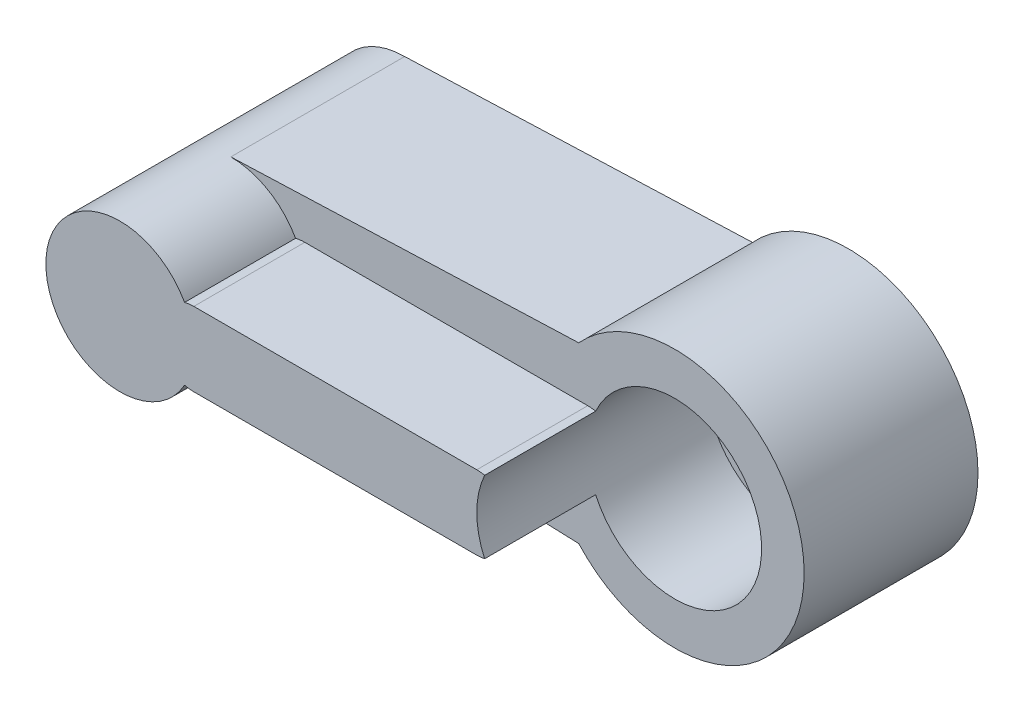
SolidWorks part; units mm, degrees
ref_plane "Front Plane" through (0, 0, 0) normal (0, 0, 1) x (1, 0, 0)
ref_plane "Top Plane" through (0, 0, 0) normal (0, 1, 0) x (1, 0, 0)
ref_plane "Right Plane" through (0, 0, 0) normal (1, 0, 0) x (0, 0, -1)
sketch "Sketch1" plane through (0, 0, 0) normal (0, 0, 1) x (1, 0, 0)
  line L4 (-10.9395, 2) -> (-1.5333, 2.35)
  line L5 (-10.9395, -2) -> (-1.5333, -2.35)
  circle A1 centre (1.0605, 0) radius 3.5
  circle A2 centre (-10.9395, 0) radius 2
  circle A3 centre (1.0605, 0) radius 2.35
  dimension "D2" = 7
  dimension "D6" = 4
  dimension "D1" = 4.7
  dimension "D5" = 4.7
  dimension "D7" = 12
  dimension "D8" = 9.4063
extrude "Boss-Extrude1" add sketch "Sketch1" along normal blind 6.7 contours A2 L5 A1 L4 | A1 | A2
sketch "Sketch2" plane through (0, 0, 6.7) normal (0, 0, 1) x (1, 0, 0)
  line L0 (-8.9395, 0) -> (-1.2895, 0) construction
  line L1 (-8.9395, 0) -> (-1.2895, 0) construction
  line L2 (-8.9395, 1) -> (-1.2895, 1)
  line L3 (-8.9395, -1) -> (-1.2895, -1)
  arc A1 (-9.1895, 0.9682) -> (-9.1895, -0.9682) centre (-10.9395, 0) ccw
  circle A2 centre (1.0605, 0) radius 2.35 construction
  arc A3 (-8.9395, 1) -> (-9.1895, 0.9682) centre (-8.9395, 0) ccw
  arc A4 (-1.2895, -1) -> (-1.0768, -0.9771) centre (-1.2895, 0) ccw
  arc A5 (-1.0768, 0.9771) -> (-1.0768, -0.9771) centre (1.0605, 0) ccw
  arc A6 (-1.0768, 0.9771) -> (-1.2895, 1) centre (-1.2895, 0) ccw
  arc A7 (-9.1895, -0.9682) -> (-8.9395, -1) centre (-8.9395, 0) ccw
  point P8 (-5.1145, 0)
extrude "Boss-Extrude2" add sketch "Sketch2" along normal blind 3
sketch "Sketch3" plane through (0, 0, 0) normal (0, 0, -1) x (-1, 0, 0)
  line L2 (10.9395, 2) -> (1.5333, 2.35)
  line L3 (1.5333, -2.35) -> (10.9395, -2)
  line L4 (10.9395, 2) -> (1.5333, 2.35)
  line L5 (1.5333, -2.35) -> (10.9395, -2)
  arc A2 (1.5333, 2.35) -> (1.5333, -2.35) centre (-1.0605, 0) ccw
  arc A3 (10.9395, -2) -> (10.9395, 2) centre (10.9395, 0) ccw
  arc A4 (1.5333, 2.35) -> (1.5333, -2.35) centre (-1.0605, 0) ccw
  arc A5 (10.9395, -2) -> (10.9395, 2) centre (10.9395, 0) ccw
  dimension "D1" = 0
extrude "Cut-Extrude1" cut sketch "Sketch3" against normal blind 2
sketch "Sketch4" plane through (0, 0, 2) normal (0, 0, -1) x (-1, 0, 0)
  circle A0 centre (-1.0605, 0) radius 1.45
  circle A1 centre (-1.0605, 0) radius 2.35
  dimension "D1" = 2.9
extrude "Boss-Extrude3" add sketch "Sketch4" against normal blind 1.5
